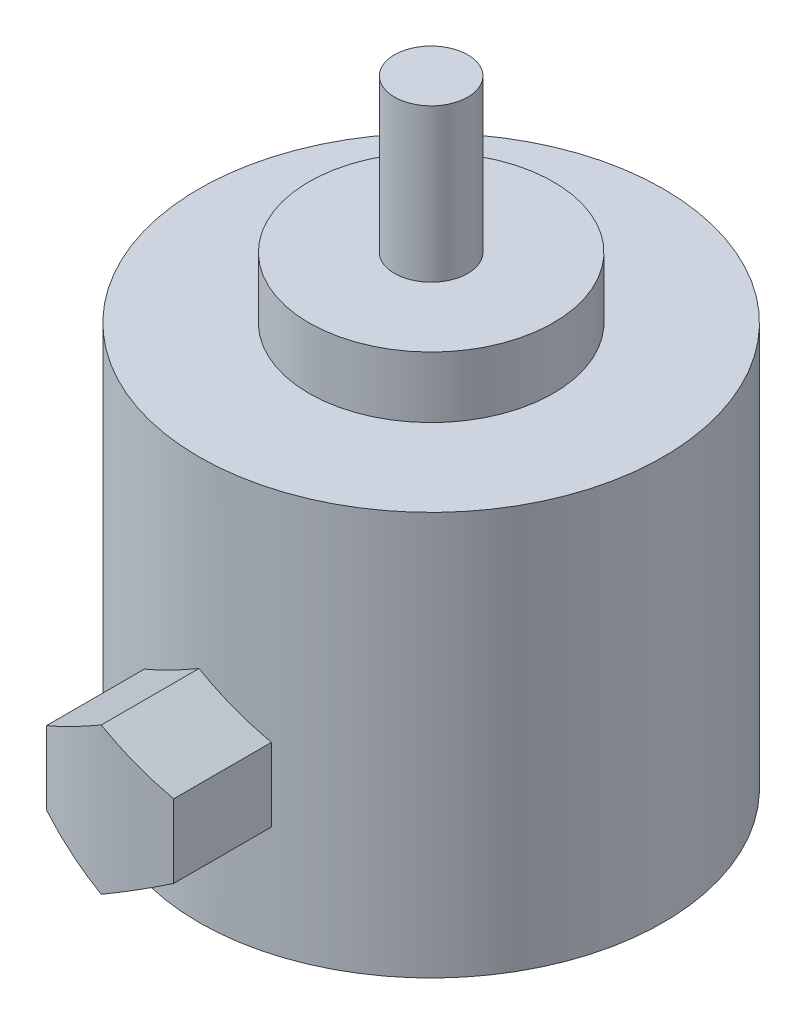
SolidWorks part; units mm, degrees
ref_plane "Alzado" through (0, 0, 0) normal (0, 0, 1) x (1, 0, 0)
ref_plane "Planta" through (0, 0, 0) normal (0, 1, 0) x (1, 0, 0)
ref_plane "Vista lateral" through (0, 0, 0) normal (1, 0, 0) x (0, 0, -1)
sketch "Croquis1" plane through (0, 0, 0) normal (0, 1, 0) x (1, 0, 0)
  circle A0 centre (0, 0) radius 19
  dimension "D1" = 38
extrude "Saliente-Extruir1" add sketch "Croquis1" along normal blind 33
sketch "Croquis2" plane through (0, 33, 0) normal (0, 1, 0) x (1, 0, 0)
  circle A0 centre (0, 0) radius 10
  dimension "D1" = 20
extrude "Saliente-Extruir2" add sketch "Croquis2" along normal blind 5
sketch "Croquis4" plane through (0, 38, 0) normal (0, 1, 0) x (1, 0, 0)
  circle A0 centre (0, 0) radius 3
  dimension "D1" = 6
extrude "Saliente-Extruir3" add sketch "Croquis4" along normal blind 12.5
sketch "Croquis6" plane through (0, 0, 0) normal (0, 0, 1) x (1, 0, 0)
  line L0 (0, 0) -> (0, 6)
  line L2 (0, 6) -> (5.1962, 9)
  line L3 (5.1962, 9) -> (5.1962, 15)
  line L4 (5.1962, 15) -> (0, 18)
  line L5 (0, 18) -> (-5.1962, 15)
  line L6 (-5.1962, 15) -> (-5.1962, 9)
  line L7 (-5.1962, 9) -> (0, 6)
  circle A1 centre (0, 12) radius 5.1962 construction
  dimension "D2" = 12
  dimension "D1" = 6
extrude "Saliente-Extruir4" add sketch "Croquis6" along normal blind 8 from surface contours L6 L7 L2 L3 L4 L5 starting at face at (0, 33, 19)
